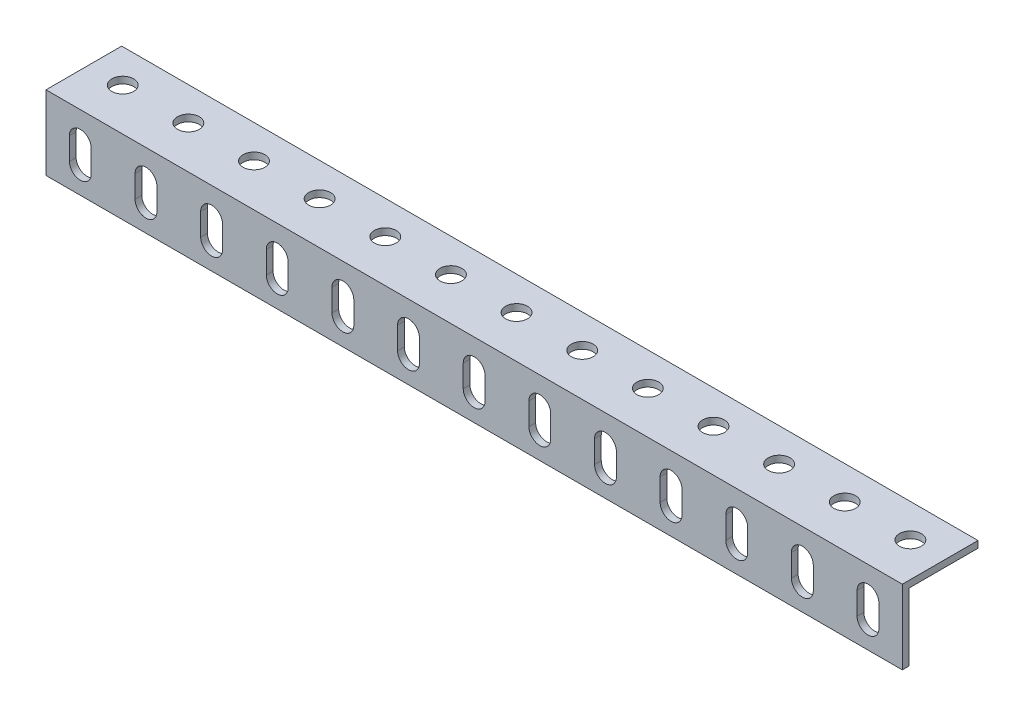
SolidWorks part; units mm, degrees
ref_plane "Front Plane" through (0, 0, 0) normal (0, 0, 1) x (1, 0, 0)
ref_plane "Top Plane" through (0, 0, 0) normal (0, 1, 0) x (1, 0, 0)
ref_plane "Right Plane" through (0, 0, 0) normal (1, 0, 0) x (0, 0, -1)
sketch "Sketch1" plane through (0, 0, 0) normal (0, 0, 1) x (1, 0, 0)
  line L0 (-76.08, 2.15) -> (-76.08, -2.15) construction
  line L1 (-73.97, 2.15) -> (-73.97, -2.15)
  line L6 (-78.19, 2.15) -> (-78.19, -2.15)
  line L7 (-65.51, 2.15) -> (-65.51, -2.15)
  line L8 (-61.29, 2.15) -> (-61.29, -2.15)
  line L9 (-63.4, 2.15) -> (-63.4, -2.15) construction
  line L10 (-52.83, 2.15) -> (-52.83, -2.15)
  line L11 (-48.61, 2.15) -> (-48.61, -2.15)
  line L12 (-50.72, 2.15) -> (-50.72, -2.15) construction
  line L13 (-40.15, 2.15) -> (-40.15, -2.15)
  line L14 (-35.93, 2.15) -> (-35.93, -2.15)
  line L15 (-38.04, 2.15) -> (-38.04, -2.15) construction
  line L16 (-27.47, 2.15) -> (-27.47, -2.15)
  line L17 (-23.25, 2.15) -> (-23.25, -2.15)
  line L18 (-25.36, 2.15) -> (-25.36, -2.15) construction
  line L19 (-14.79, 2.15) -> (-14.79, -2.15)
  line L20 (-10.57, 2.15) -> (-10.57, -2.15)
  line L21 (-12.68, 2.15) -> (-12.68, -2.15) construction
  line L22 (-2.11, 2.15) -> (-2.11, -2.15)
  line L23 (2.11, 2.15) -> (2.11, -2.15)
  line L24 (0, 2.15) -> (0, -2.15) construction
  line L25 (10.57, 2.15) -> (10.57, -2.15)
  line L26 (14.79, 2.15) -> (14.79, -2.15)
  line L27 (12.68, 2.15) -> (12.68, -2.15) construction
  line L28 (23.25, 2.15) -> (23.25, -2.15)
  line L29 (27.47, 2.15) -> (27.47, -2.15)
  line L30 (25.36, 2.15) -> (25.36, -2.15) construction
  line L31 (35.93, 2.15) -> (35.93, -2.15)
  line L32 (40.15, 2.15) -> (40.15, -2.15)
  line L33 (38.04, 2.15) -> (38.04, -2.15) construction
  line L34 (48.61, 2.15) -> (48.61, -2.15)
  line L35 (52.83, 2.15) -> (52.83, -2.15)
  line L36 (50.72, 2.15) -> (50.72, -2.15) construction
  line L37 (61.29, 2.15) -> (61.29, -2.15)
  line L38 (65.51, 2.15) -> (65.51, -2.15)
  line L39 (63.4, 2.15) -> (63.4, -2.15) construction
  line L40 (73.97, 2.15) -> (73.97, -2.15)
  line L41 (78.19, 2.15) -> (78.19, -2.15)
  line L42 (76.08, 2.15) -> (76.08, -2.15) construction
  line L44 (-82.71, 7.56) -> (82.71, 7.56)
  line L45 (-82.71, 7.56) -> (-82.71, -6.78)
  line L46 (-82.71, -6.78) -> (82.71, -6.78)
  line L47 (82.71, 7.56) -> (82.71, -6.78)
  arc A0 (-73.97, 2.15) -> (-78.19, 2.15) centre (-76.08, 2.15) ccw
  arc A1 (-78.19, -2.15) -> (-73.97, -2.15) centre (-76.08, -2.15) ccw
  arc A2 (-61.29, 2.15) -> (-65.51, 2.15) centre (-63.4, 2.15) ccw
  arc A3 (-65.51, -2.15) -> (-61.29, -2.15) centre (-63.4, -2.15) ccw
  arc A4 (-48.61, 2.15) -> (-52.83, 2.15) centre (-50.72, 2.15) ccw
  arc A5 (-52.83, -2.15) -> (-48.61, -2.15) centre (-50.72, -2.15) ccw
  arc A6 (-35.93, 2.15) -> (-40.15, 2.15) centre (-38.04, 2.15) ccw
  arc A7 (-40.15, -2.15) -> (-35.93, -2.15) centre (-38.04, -2.15) ccw
  arc A8 (-23.25, 2.15) -> (-27.47, 2.15) centre (-25.36, 2.15) ccw
  arc A9 (-27.47, -2.15) -> (-23.25, -2.15) centre (-25.36, -2.15) ccw
  arc A10 (-10.57, 2.15) -> (-14.79, 2.15) centre (-12.68, 2.15) ccw
  arc A11 (-14.79, -2.15) -> (-10.57, -2.15) centre (-12.68, -2.15) ccw
  arc A12 (2.11, 2.15) -> (-2.11, 2.15) centre (0, 2.15) ccw
  arc A13 (-2.11, -2.15) -> (2.11, -2.15) centre (0, -2.15) ccw
  arc A14 (14.79, 2.15) -> (10.57, 2.15) centre (12.68, 2.15) ccw
  arc A15 (10.57, -2.15) -> (14.79, -2.15) centre (12.68, -2.15) ccw
  arc A16 (27.47, 2.15) -> (23.25, 2.15) centre (25.36, 2.15) ccw
  arc A17 (23.25, -2.15) -> (27.47, -2.15) centre (25.36, -2.15) ccw
  arc A18 (40.15, 2.15) -> (35.93, 2.15) centre (38.04, 2.15) ccw
  arc A19 (35.93, -2.15) -> (40.15, -2.15) centre (38.04, -2.15) ccw
  arc A20 (52.83, 2.15) -> (48.61, 2.15) centre (50.72, 2.15) ccw
  arc A21 (48.61, -2.15) -> (52.83, -2.15) centre (50.72, -2.15) ccw
  arc A22 (65.51, 2.15) -> (61.29, 2.15) centre (63.4, 2.15) ccw
  arc A23 (61.29, -2.15) -> (65.51, -2.15) centre (63.4, -2.15) ccw
  arc A24 (78.19, 2.15) -> (73.97, 2.15) centre (76.08, 2.15) ccw
  arc A25 (73.97, -2.15) -> (78.19, -2.15) centre (76.08, -2.15) ccw
  point P2 (-76.08, 0)
  point P7 (-76.08, 4.26)
  point P8 (-76.08, -4.26)
  point P9 (-73.97, 0)
  point P10 (-78.19, 0)
  point P14 (-63.4, 0)
  point P21 (-50.72, 0)
  point P28 (-38.04, 0)
  point P35 (-25.36, 0)
  point P42 (-12.68, 0)
  point P49 (0, 0)
  point P56 (12.68, 0)
  point P63 (25.36, 0)
  point P70 (38.04, 0)
  point P77 (50.72, 0)
  point P84 (63.4, 0)
  point P91 (76.08, 0)
  dimension "D1" = 8.52
  dimension "D2" = 4.22
  dimension "D4" = 8.46
  dimension "D5" = 4.52
  dimension "D6" = 4.52
  dimension "D7" = 2.52
  dimension "D8" = 3.3
  dimension "D3" = 13
extrude "Boss-Extrude1" add sketch "Sketch1" against normal blind 1.3
sketch "Sketch3" plane through (0, 7.56, 0) normal (0, 1, 0) x (1, 0, 0)
  line L0 (-7.887, 0) -> (7.887, 0) construction
  line L1 (-82.71, 0) -> (82.71, 0)
  line L2 (-82.71, 0) -> (-82.71, 14.62)
  line L3 (-82.71, 14.62) -> (82.71, 14.62)
  line L4 (82.71, 0) -> (82.71, 14.62)
  line L5 (-82.71, 1.3) -> (-82.71, 0) construction
  line L6 (82.71, 1.3) -> (82.71, 0) construction
  circle A0 centre (-76.08, 8.19) radius 2.11
  circle A2 centre (-63.4, 8.19) radius 2.11
  circle A3 centre (-50.72, 8.19) radius 2.11
  circle A4 centre (-38.04, 8.19) radius 2.11
  circle A5 centre (-25.36, 8.19) radius 2.11
  circle A6 centre (-12.68, 8.19) radius 2.11
  circle A7 centre (0, 8.19) radius 2.11
  circle A8 centre (12.68, 8.19) radius 2.11
  circle A9 centre (25.36, 8.19) radius 2.11
  circle A10 centre (38.04, 8.19) radius 2.11
  circle A11 centre (50.72, 8.19) radius 2.11
  circle A12 centre (63.4, 8.19) radius 2.11
  circle A13 centre (76.08, 8.19) radius 2.11
  point P13 (-78.19, 8.19)
  point P14 (-65.51, 8.19)
  point P38 (-73.97, 8.19)
  point P39 (-76.08, 10.3)
  dimension "D1" = 4.22
  dimension "D2" = 4.52
  dimension "D4" = 8.46
  dimension "D5" = 4.32
  dimension "D6" = 14.62
  dimension "D3" = 13
extrude "Boss-Extrude2" add sketch "Sketch3" against normal blind 1.3
